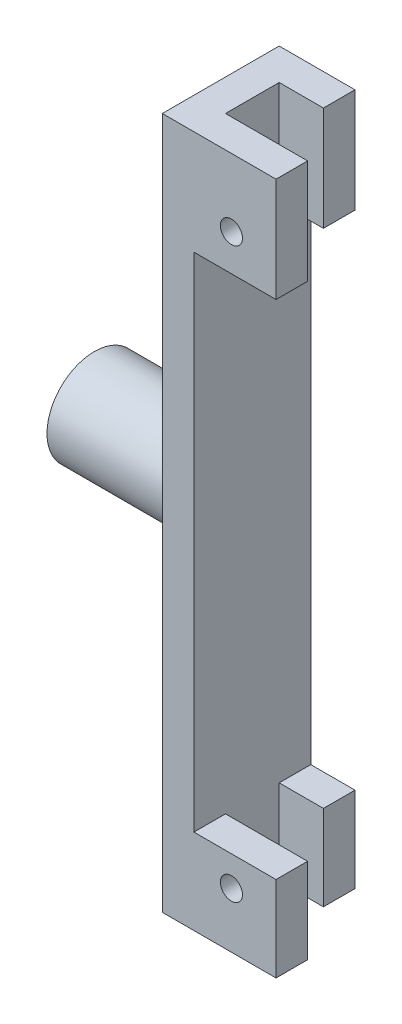
SolidWorks part; units mm, degrees
ref_plane "정면" through (0, 0, 0) normal (0, 0, 1) x (1, 0, 0)
ref_plane "윗면" through (0, 0, 0) normal (0, 1, 0) x (1, 0, 0)
ref_plane "우측면" through (0, 0, 0) normal (1, 0, 0) x (0, 0, -1)
sketch "스케치1" plane through (0, 0, 0) normal (0, 0, 1) x (1, 0, 0)
  line L1 (18, -109.5) -> (-18, -109.5)
  line L2 (18, -109.5) -> (18, 109.5)
  line L3 (18, 109.5) -> (-18, 109.5)
  line L4 (-18, -109.5) -> (-18, 109.5)
  line L5 (18, -109.5) -> (-18, 109.5) construction
  line L6 (18, 109.5) -> (-18, -109.5) construction
  point P0 (0, 0)
  dimension "D1" = 219
  dimension "D2" = 36
extrude "보스-돌출1" add sketch "스케치1" along normal blind 37
sketch "스케치2" plane through (0, 0, 0) normal (0, 0, 1) x (1, 0, 0)
  line L0 (18, -109.5) -> (18, 109.5) construction
  line L1 (-8, 76.5) -> (72.768, 76.5)
  line L2 (-8, 76.5) -> (-8, -82.5)
  line L3 (-8, -82.5) -> (72.768, -82.5)
  line L4 (72.768, 76.5) -> (72.768, -82.5)
  line L5 (18, 109.5) -> (-18, 109.5) construction
  dimension "D1" = 26
  dimension "D2" = 159
  dimension "D3" = 33
extrude "컷-돌출1" cut sketch "스케치2" along normal through all
sketch "스케치9" plane through (0, 0, 0) normal (0, 0, 1) x (1, 0, 0)
  line L0 (18, 76.5) -> (18, 109.5) construction
  line L1 (-8, 109.5) -> (18, 109.5)
  line L2 (-8, 109.5) -> (-8, -109.5)
  line L3 (-8, -109.5) -> (18, -109.5)
  line L4 (18, 109.5) -> (18, -109.5)
  line L5 (18, 109.5) -> (-18, 109.5) construction
  dimension "D1" = 26
  dimension "D2" = 219
extrude "컷-돌출7" cut sketch "스케치9" along normal blind 17 from offset 10
sketch "스케치10" plane through (0, 0, 0) normal (0, 0, 1) x (1, 0, 0)
  line L0 (18, 76.5) -> (18, 109.5) construction
  line L1 (18, 126.5) -> (6, 126.5)
  line L2 (18, 126.5) -> (18, -109.5)
  line L3 (18, -109.5) -> (6, -109.5)
  line L4 (6, 126.5) -> (6, -109.5)
  line L5 (-18, -109.5) -> (18, -109.5) construction
  dimension "D1" = 236
  dimension "D2" = 12
extrude "컷-돌출8" cut sketch "스케치10" along normal blind 17
sketch "스케치11" plane through (0, 0, 0) normal (0, 0, 1) x (1, 0, 0)
  line L1 (-18, 109.5) -> (-18, -109.5) construction
  line L4 (18, 76.5) -> (-8, 76.5) construction
  line L5 (-8, -82.5) -> (18, -82.5) construction
  circle A0 centre (3.8782, 88) radius 3.5
  circle A1 centre (3.8782, -92) radius 3.5
  dimension "D1" = 7
  dimension "D2" = 8
  dimension "D3" = 18.3782
  dimension "D5" = 9.5
extrude "컷-돌출11" cut sketch "스케치11" against normal blind 17 from surface at 37 starting at face at (2.5, -1.5, 37)
ref_plane "평면1" through (-18, 0, 0) normal (-1, 0, 0) x (0, 0, 1)
sketch "스케치25" plane through (-18, 0, 0) normal (-1, 0, 0) x (0, 0, 1)
  circle A0 centre (18.5, 0) radius 15
extrude "보스-돌출3" add sketch "스케치25" along normal blind 40
